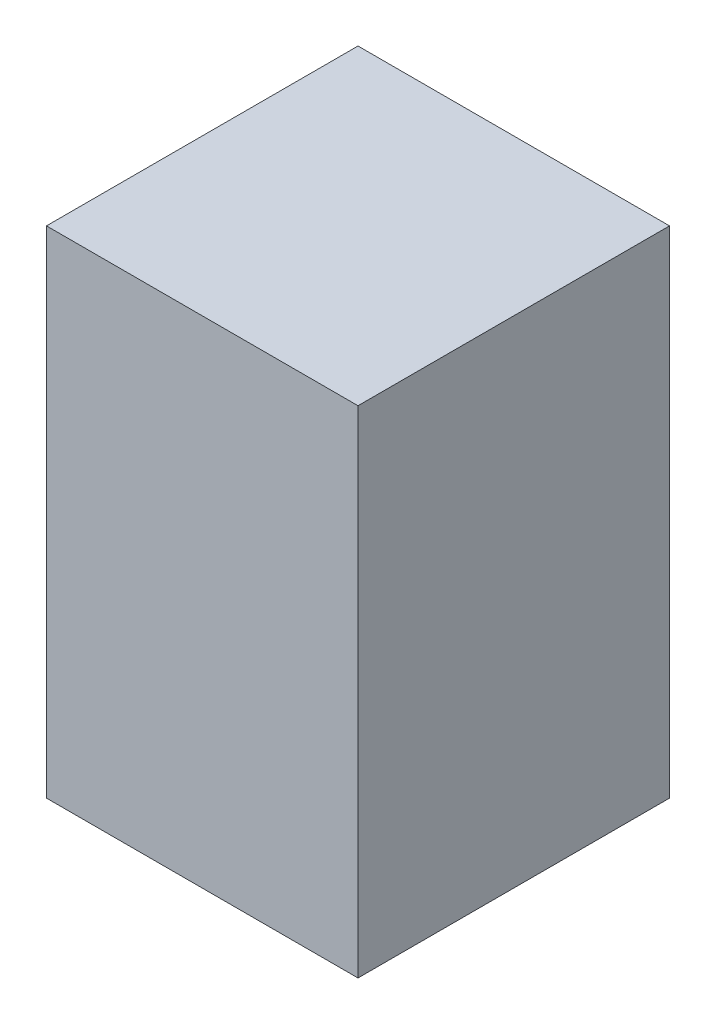
SolidWorks part; units mm, degrees
ref_plane "Front Plane" through (0, 0, 0) normal (0, 0, 1) x (1, 0, 0)
ref_plane "Top Plane" through (0, 0, 0) normal (0, 1, 0) x (1, 0, 0)
ref_plane "Right Plane" through (0, 0, 0) normal (1, 0, 0) x (0, 0, -1)
sketch "Sketch1" plane through (0, 0, 0) normal (0, 1, 0) x (1, 0, 0)
  line L1 (-0.11, -0.11) -> (0.11, -0.11)
  line L2 (-0.11, -0.11) -> (-0.11, 0.11)
  line L3 (-0.11, 0.11) -> (0.11, 0.11)
  line L4 (0.11, -0.11) -> (0.11, 0.11)
  line L5 (-0.11, -0.11) -> (0.11, 0.11) construction
  line L6 (-0.11, 0.11) -> (0.11, -0.11) construction
  point P0 (0, 0)
  dimension "D1" = 0.22
  dimension "D2" = 0.22
extrude "Boss-Extrude1" add sketch "Sketch1" along normal blind 0.35
